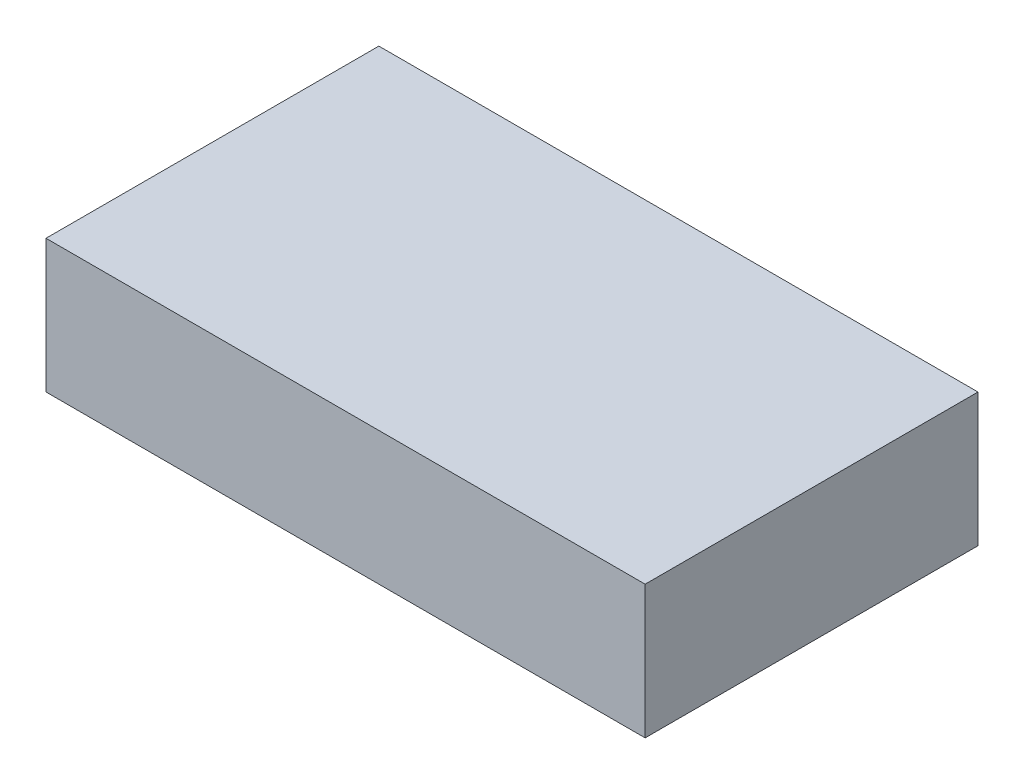
SolidWorks part; units mm, degrees
ref_plane "Front Plane" through (0, 0, 0) normal (0, 0, 1) x (1, 0, 0)
ref_plane "Top Plane" through (0, 0, 0) normal (0, 1, 0) x (1, 0, 0)
ref_plane "Right Plane" through (0, 0, 0) normal (1, 0, 0) x (0, 0, -1)
sketch "Sketch1" plane through (0, 0, 0) normal (0, 1, 0) x (1, 0, 0)
  line L1 (-22.5, 12.5) -> (22.5, 12.5)
  line L2 (-22.5, 12.5) -> (-22.5, -12.5)
  line L3 (-22.5, -12.5) -> (22.5, -12.5)
  line L4 (22.5, 12.5) -> (22.5, -12.5)
  line L5 (-22.5, 12.5) -> (22.5, -12.5) construction
  line L6 (-22.5, -12.5) -> (22.5, 12.5) construction
  point P0 (0, 0)
  dimension "D1" = 45
  dimension "D2" = 25
extrude "Boss-Extrude1" add sketch "Sketch1" along normal blind 10
